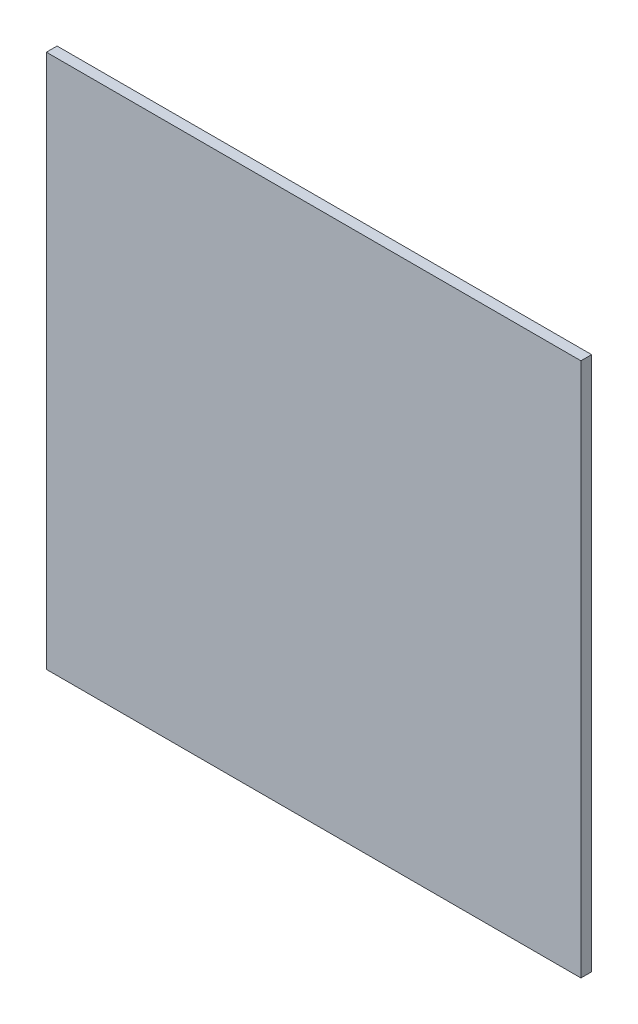
SolidWorks part; units mm, degrees
ref_plane "Front Plane" through (0, 0, 0) normal (0, 0, 1) x (1, 0, 0)
ref_plane "Top Plane" through (0, 0, 0) normal (0, 1, 0) x (1, 0, 0)
ref_plane "Right Plane" through (0, 0, 0) normal (1, 0, 0) x (0, 0, -1)
sketch "Sketch1" plane through (0, 0, 0) normal (0, 0, 1) x (1, 0, 0)
  line L1 (-125, 125) -> (125, 125)
  line L2 (-125, 125) -> (-125, -125)
  line L3 (-125, -125) -> (125, -125)
  line L4 (125, 125) -> (125, -125)
  line L5 (-125, 125) -> (125, -125) construction
  line L6 (-125, -125) -> (125, 125) construction
  point P0 (0, 0)
  dimension "D1" = 250
  dimension "D2" = 250
extrude "Boss-Extrude1" add sketch "Sketch1" along normal blind 5
